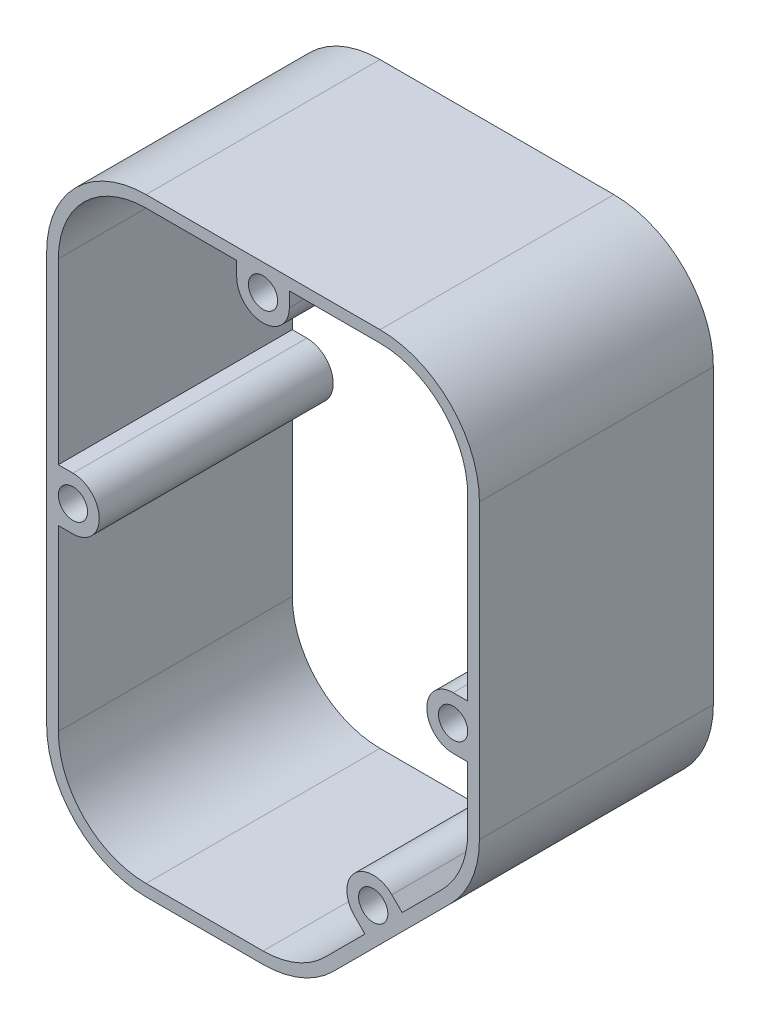
SolidWorks part; units mm, degrees
ref_plane "Front Plane" through (0, 0, 0) normal (0, 0, 1) x (1, 0, 0)
ref_plane "Top Plane" through (0, 0, 0) normal (0, 1, 0) x (1, 0, 0)
ref_plane "Right Plane" through (0, 0, 0) normal (1, 0, 0) x (0, 0, -1)
sketch "Sketch1" plane through (0, 0, 0) normal (0, 0, 1) x (1, 0, 0)
  line L0 (89.6607, -42.5) -> (108.1607, -42.5) construction
  line L1 (89.6607, -68.5) -> (89.6607, -16.5) construction
  line L2 (108.1607, -25) -> (108.1607, -50) construction
  line L3 (71.1607, -25) -> (71.1607, -60)
  line L4 (94.964, -65.3033) -> (104.964, -55.3033)
  line L5 (107.1607, -50) -> (107.1607, -25)
  line L6 (99.6607, -17.5) -> (74.609, -17.5)
  line L7 (77.4609, 46.385) -> (86.2252, 45.6009)
  line L8 (-86.2252, 45.6009) -> (-77.4609, 46.385)
  line L9 (-74.609, -17.5) -> (-99.6607, -17.5)
  line L10 (-89.6607, -68.5) -> (-51.2214, -68.5)
  line L11 (51.2214, -68.5) -> (89.6607, -68.5)
  line L12 (95.6711, -66.0104) -> (105.6711, -56.0104)
  line L13 (108.1607, -50) -> (108.1607, -25)
  line L14 (99.6607, -16.5) -> (74.609, -16.5)
  line L15 (77.3718, 45.3889) -> (86.1361, 44.6049)
  line L16 (-86.1361, 44.6049) -> (-77.3718, 45.3889)
  line L17 (-74.609, -16.5) -> (-99.6607, -16.5)
  line L18 (-108.1607, -25) -> (-108.1607, -50)
  line L19 (-105.6711, -56.0104) -> (-95.6711, -66.0104)
  line L20 (-89.6607, -68.5) -> (-51.2214, -68.5)
  line L21 (51.2214, -68.5) -> (89.6607, -68.5)
  line L22 (95.6711, -66.0104) -> (105.6711, -56.0104)
  line L23 (108.1607, -50) -> (108.1607, -25)
  line L24 (99.6607, -16.5) -> (74.609, -16.5)
  line L25 (77.3718, 45.3889) -> (86.1361, 44.6049)
  line L26 (-86.1361, 44.6049) -> (-77.3718, 45.3889)
  line L27 (-74.609, -16.5) -> (-99.6607, -16.5)
  line L28 (-108.1607, -25) -> (-108.1607, -50)
  line L29 (-105.6711, -56.0104) -> (-95.6711, -66.0104)
  line L30 (-107.1607, -25) -> (-107.1607, -50)
  line L31 (-104.964, -55.3033) -> (-94.964, -65.3033)
  line L32 (-89.6607, -67.5) -> (-51.2214, -67.5)
  line L33 (51.2214, -67.5) -> (89.6607, -67.5)
  line L34 (72.1607, -25) -> (72.1607, -60)
  line L35 (87.4107, -18.75) -> (87.4107, -17.5)
  line L36 (91.9107, -18.75) -> (91.9107, -17.5)
  line L37 (71.1607, -42.5) -> (89.6607, -42.5) construction
  line L38 (73.4107, -40.25) -> (72.1607, -40.25)
  line L39 (73.4107, -44.75) -> (72.1607, -44.75)
  line L40 (105.9107, -44.75) -> (107.1607, -44.75)
  line L41 (105.9107, -40.25) -> (107.1607, -40.25)
  line L42 (100.6711, -61.0104) -> (72.1607, -32.5) construction
  line L43 (97.4891, -61.0104) -> (98.373, -61.8943)
  line L44 (100.6711, -57.8284) -> (101.555, -58.7123)
  circle A0 centre (99.6607, -50) radius 3.5 construction
  circle A1 centre (89.6607, -60) radius 3.5 construction
  circle A2 centre (79.6607, -50) radius 3.5 construction
  circle A3 centre (89.6607, -40) radius 3.5 construction
  circle A4 centre (99.6607, -25) radius 3.5 construction
  circle A5 centre (79.6607, -25) radius 3.5 construction
  circle A6 centre (99.6607, -50) radius 3.5
  circle A7 centre (89.6607, -60) radius 3.5
  circle A8 centre (79.6607, -50) radius 3.5
  circle A9 centre (89.6607, -40) radius 3.5
  circle A10 centre (99.6607, -25) radius 3.5
  circle A11 centre (79.6607, -25) radius 3.5
  circle A12 centre (99.6607, -25) radius 8.5
  arc A14 (-51.2214, -68.5) -> (-44.7781, -65.5439) centre (-51.2214, -60) ccw
  arc A15 (44.7781, -65.5439) -> (-44.7781, -65.5439) centre (0, -104.0719) ccw
  arc A16 (44.7781, -65.5439) -> (51.2214, -68.5) centre (51.2214, -60) ccw
  arc A17 (89.6607, -68.5) -> (95.6711, -66.0104) centre (89.6607, -60) ccw
  arc A18 (105.6711, -56.0104) -> (108.1607, -50) centre (99.6607, -50) ccw
  arc A19 (108.1607, -25) -> (99.6607, -16.5) centre (99.6607, -25) ccw
  arc A20 (77.3718, 45.3889) -> (74.609, -16.5) centre (74.609, 14.5061) ccw
  arc A21 (86.1361, 44.6049) -> (89.3936, 73.4134) centre (87.4281, 59.0472) ccw
  arc A22 (89.3936, 73.4134) -> (-89.3936, 73.4134) centre (0, -580) ccw
  arc A23 (-89.3936, 73.4134) -> (-86.1361, 44.6049) centre (-87.4281, 59.0472) ccw
  arc A24 (-74.609, -16.5) -> (-77.3718, 45.3889) centre (-74.609, 14.5061) ccw
  arc A25 (-99.6607, -16.5) -> (-108.1607, -25) centre (-99.6607, -25) ccw
  arc A26 (-108.1607, -50) -> (-105.6711, -56.0104) centre (-99.6607, -50) ccw
  arc A27 (-95.6711, -66.0104) -> (-89.6607, -68.5) centre (-89.6607, -60) ccw
  arc A28 (-51.2214, -68.5) -> (-44.7781, -65.5439) centre (-51.2214, -60) ccw
  arc A29 (44.7781, -65.5439) -> (-44.7781, -65.5439) centre (0, -104.0719) ccw
  arc A30 (44.7781, -65.5439) -> (51.2214, -68.5) centre (51.2214, -60) ccw
  arc A31 (89.6607, -68.5) -> (95.6711, -66.0104) centre (89.6607, -60) ccw
  arc A32 (105.6711, -56.0104) -> (108.1607, -50) centre (99.6607, -50) ccw
  arc A33 (108.1607, -25) -> (99.6607, -16.5) centre (99.6607, -25) ccw
  arc A34 (77.3718, 45.3889) -> (74.609, -16.5) centre (74.609, 14.5061) ccw
  arc A35 (86.1361, 44.6049) -> (89.3936, 73.4134) centre (87.4281, 59.0472) ccw
  arc A36 (89.3936, 73.4134) -> (-89.3936, 73.4134) centre (0, -580) ccw
  arc A37 (-89.3936, 73.4134) -> (-86.1361, 44.6049) centre (-87.4281, 59.0472) ccw
  arc A38 (-74.609, -16.5) -> (-77.3718, 45.3889) centre (-74.609, 14.5061) ccw
  arc A39 (-99.6607, -16.5) -> (-108.1607, -25) centre (-99.6607, -25) ccw
  arc A40 (-108.1607, -50) -> (-105.6711, -56.0104) centre (-99.6607, -50) ccw
  arc A41 (-95.6711, -66.0104) -> (-89.6607, -68.5) centre (-89.6607, -60) ccw
  circle A42 centre (79.6607, -25) radius 8.5
  circle A43 centre (79.6607, -60) radius 8.5
  arc A44 (104.964, -55.3033) -> (107.1607, -50) centre (99.6607, -50) ccw
  arc A45 (107.1607, -25) -> (99.6607, -17.5) centre (99.6607, -25) ccw
  arc A46 (77.4609, 46.385) -> (74.609, -17.5) centre (74.609, 14.5061) ccw
  arc A47 (86.2252, 45.6009) -> (89.258, 72.4226) centre (87.4281, 59.0472) ccw
  arc A48 (89.258, 72.4226) -> (-89.258, 72.4226) centre (0, -580) ccw
  arc A49 (-89.258, 72.4226) -> (-86.2252, 45.6009) centre (-87.4281, 59.0472) ccw
  arc A50 (-74.609, -17.5) -> (-77.4609, 46.385) centre (-74.609, 14.5061) ccw
  arc A51 (-99.6607, -17.5) -> (-107.1607, -25) centre (-99.6607, -25) ccw
  arc A52 (-107.1607, -50) -> (-104.964, -55.3033) centre (-99.6607, -50) ccw
  arc A53 (-94.964, -65.3033) -> (-89.6607, -67.5) centre (-89.6607, -60) ccw
  arc A54 (-51.2214, -67.5) -> (-45.5362, -64.8917) centre (-51.2214, -60) ccw
  arc A55 (45.5362, -64.8917) -> (-45.5362, -64.8917) centre (0, -104.0719) ccw
  arc A56 (45.5362, -64.8917) -> (51.2214, -67.5) centre (51.2214, -60) ccw
  arc A57 (89.6607, -67.5) -> (94.964, -65.3033) centre (89.6607, -60) ccw
  circle A58 centre (79.6607, -25) radius 7.5
  circle A59 centre (79.6607, -60) radius 7.5
  circle A60 centre (89.6607, -18.75) radius 1.25
  circle A61 centre (89.6607, -18.75) radius 2.25
  circle A62 centre (73.4107, -42.5) radius 1.25
  circle A63 centre (73.4107, -42.5) radius 2.25
  circle A64 centre (105.9107, -42.5) radius 1.25
  circle A65 centre (105.9107, -42.5) radius 2.25
  circle A66 centre (99.0801, -59.4194) radius 1.25
  circle A67 centre (99.0801, -59.4194) radius 2.25
  dimension "D3" = 2.5
  dimension "D1" = 0
  dimension "D2" = 1
extrude "Boss-Extrude1" add sketch "Sketch1" along normal blind 20 contours A67 L4 A57 L33 A43 L21 A31 L22 | L4 A67 A66 | L4 A67 | A67 L43 L4 | A67 L4 L44 | A67 L22 A32 L23 A65 L5 A44 L4 | A65 L5 | A65 L5 A64 | L5 A65 L40 | L41 A65 L5 | L5 A65 L23 A12 | A45 L5 A12 L6 | A61 L6 A12 L24 | L6 A61 | A61 L36 L6 | A61 L6 A60 | A61 L6 L35 | A61 L24 A42 L6 | A42 L6 | A58 L6 A42 L34 | A63 L34 A42 L3 | L34 A63 | A63 L38 L34 | A63 L34 A62 | A63 L34 L39 | A63 L3 A43 L34 | A59 L34 A43 L33 | L33 A43
